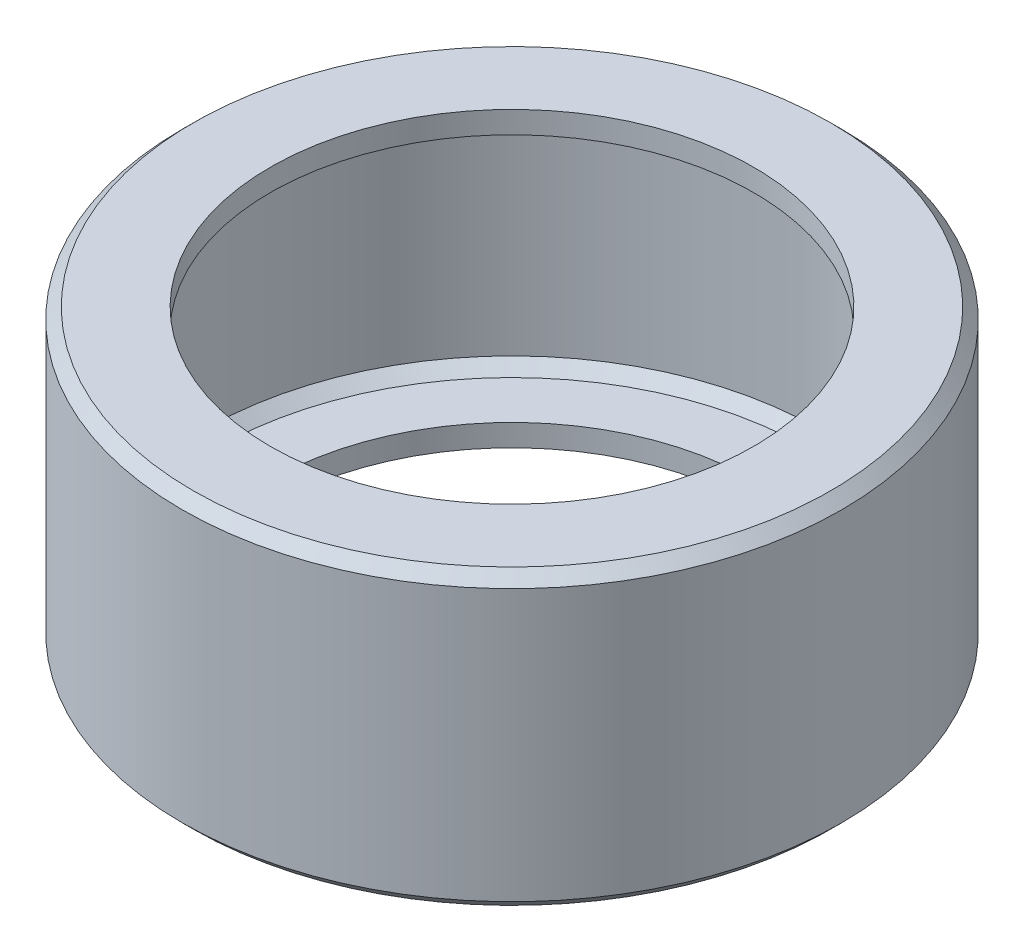
SolidWorks part; units mm, degrees
material "Custom Stainless Steel 1"
ref_plane "Front Plane" through (0, 0, 0) normal (0, 0, 1) x (1, 0, 0)
ref_plane "Top Plane" through (0, 0, 0) normal (0, 1, 0) x (1, 0, 0)
ref_plane "Right Plane" through (0, 0, 0) normal (1, 0, 0) x (0, 0, -1)
sketch "Sketch1" plane through (0, 0, 0) normal (0, 1, 0) x (1, 0, 0)
  circle A0 centre (0, 0) radius 4.5
  circle A1 centre (0, 0) radius 4.5 construction
  circle A2 centre (0, 0) radius 4.2
  circle A3 centre (0, 0) radius 4.2 construction
extrude "Boss-Extrude1" add sketch "Sketch1" along normal blind 1.7
sketch "Sketch2" plane through (0, 1.7, 0) normal (0, 1, 0) x (1, 0, 0)
  circle A0 centre (0, 0) radius 4.5
  circle A1 centre (0, 0) radius 4.5 construction
  circle A2 centre (0, 0) radius 3.3
  circle A3 centre (0, 0) radius 3.3 construction
extrude "Boss-Extrude2" add sketch "Sketch2" along normal blind 0.3
chamfer "Chamfer1" distance 0.15 angle 45 1 edges at (0, 2, 4.5)
chamfer "Chamfer2" distance 0.15 angle 45 1 edges at (0, 1.7, 4.2)
mirror "Mirror1" about plane through (0, 0, 0) normal (0, 1, 0) of bodies 102
sketch3d "3DSketch1"
  line L0 (0, 2, 0) -> (0, -2, 0) construction
